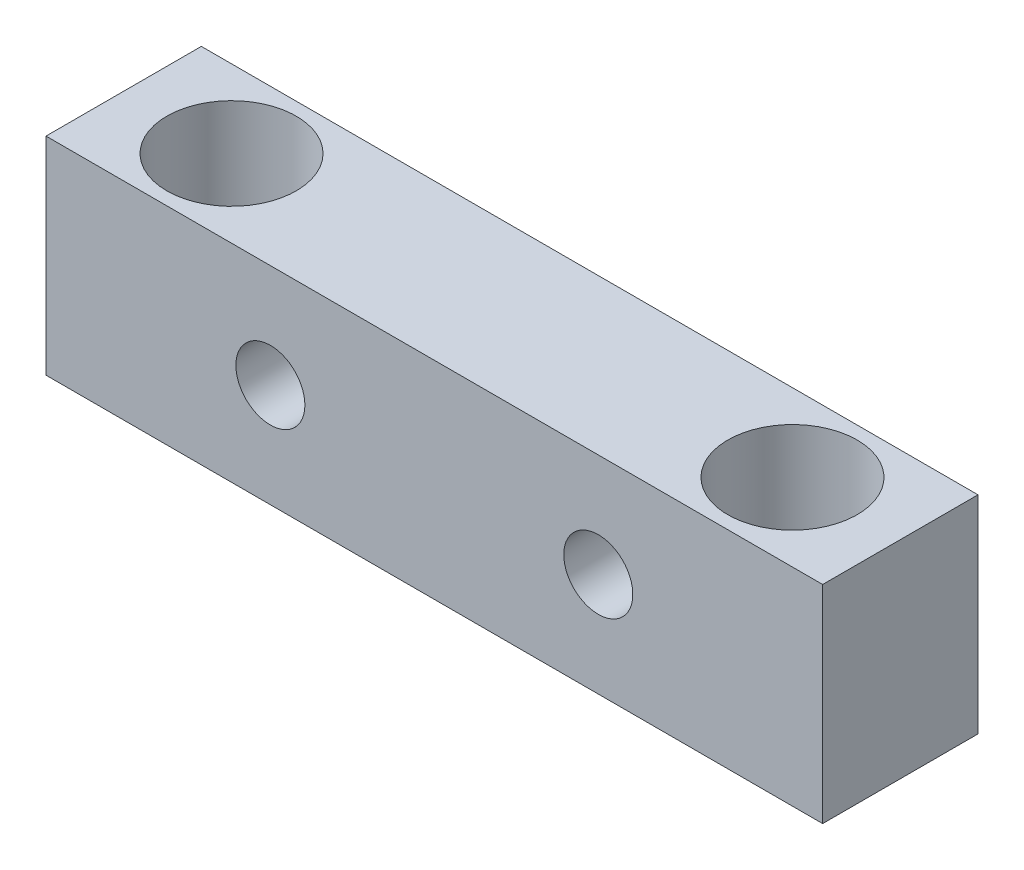
SolidWorks part; units mm, degrees
ref_plane "Front Plane" through (0, 0, 0) normal (0, 0, 1) x (1, 0, 0)
ref_plane "Top Plane" through (0, 0, 0) normal (0, 1, 0) x (1, 0, 0)
ref_plane "Right Plane" through (0, 0, 0) normal (1, 0, 0) x (0, 0, -1)
sketch "Sketch1" plane through (0, 0, 0) normal (0, 0, 1) x (1, 0, 0)
  line L0 (0, 0) -> (0, 14.0353) construction
  line L1 (-45, -12) -> (45, -12)
  line L2 (-45, -12) -> (-45, 12)
  line L3 (-45, 12) -> (45, 12)
  line L4 (45, -12) -> (45, 12)
  line L5 (-45, -12) -> (45, 12) construction
  line L6 (-45, 12) -> (45, -12) construction
  line L7 (0, 0) -> (-19, 0) construction
  circle A0 centre (-19, 0) radius 4
  circle A1 centre (19, 0) radius 4
  point P0 (0, 0)
  dimension "D1" = 8
  dimension "D4" = 38
  dimension "D2" = 24
  dimension "D3" = 90
extrude "Boss-Extrude1" add sketch "Sketch1" along normal blind 18
sketch "Sketch2" plane through (0, 12, 0) normal (0, 1, 0) x (1, 0, 0)
  line L0 (-45, -9) -> (45, -9) construction
  line L1 (-45, -18) -> (-45, 0) construction
  line L2 (45, -18) -> (45, 0) construction
  line L3 (0, 0) -> (0, -18) construction
  line L4 (45, 0) -> (-45, 0) construction
  line L5 (45, -18) -> (-45, -18) construction
  circle A0 centre (-32.5, -9) radius 7.5
  circle A1 centre (32.5, -9) radius 7.5
  dimension "D1" = 15
  dimension "D2" = 65
extrude "Cut-Extrude3" cut sketch "Sketch2" against normal through all
